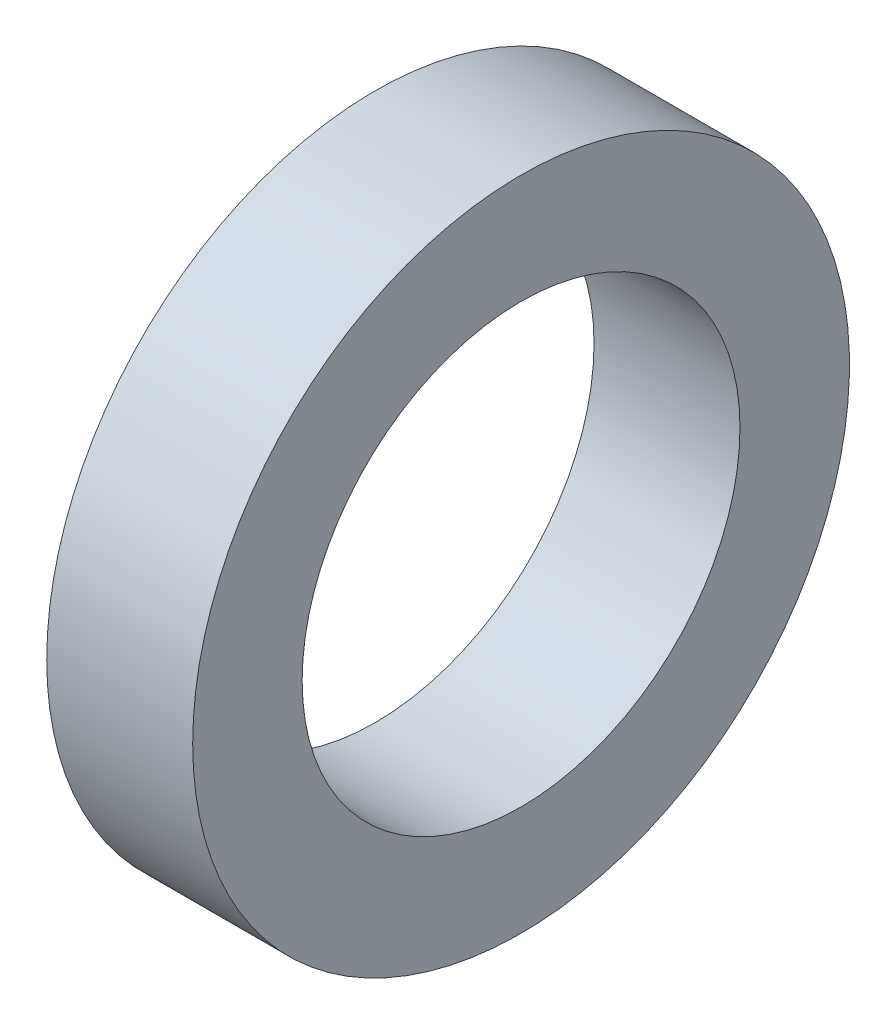
SolidWorks part; units mm, degrees
ref_plane "Front Plane" through (0, 0, 0) normal (0, 0, 1) x (1, 0, 0)
ref_plane "Top Plane" through (0, 0, 0) normal (0, 1, 0) x (1, 0, 0)
ref_plane "Right Plane" through (0, 0, 0) normal (1, 0, 0) x (0, 0, -1)
sketch "Sketch2" plane through (0, 0, 0) normal (0, 0, 1) x (1, 0, 0)
  line L0 (0, 0) -> (7.5593, 0) construction
  line L1 (0, 9) -> (4, 9)
  line L2 (0, 9) -> (0, 6)
  line L3 (0, 6) -> (4, 6)
  line L4 (4, 9) -> (4, 6)
  point P7 (0, 0)
  dimension "D1" = 6
  dimension "D2" = 9
  dimension "D3" = 4
revolve "Revolve1" add sketch "Sketch2" angle 360 about L0
